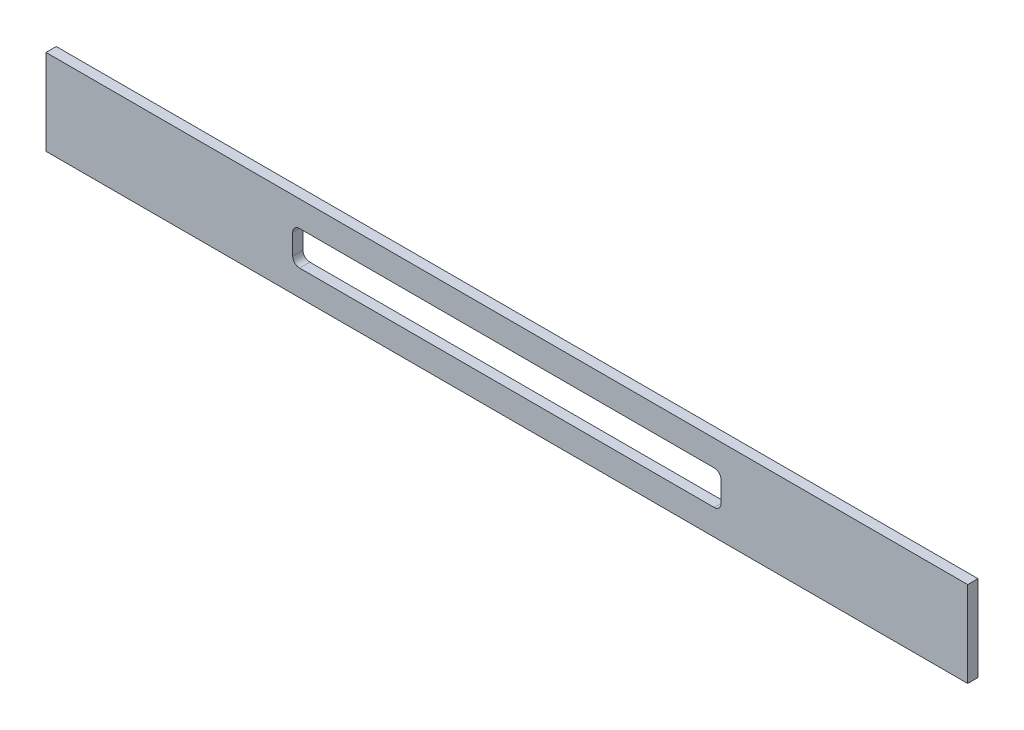
SolidWorks part; units mm, degrees
material "Клен"
ref_plane "Спереди" through (0, 0, 0) normal (0, 0, 1) x (1, 0, 0)
ref_plane "Сверху" through (0, 0, 0) normal (0, 1, 0) x (1, 0, 0)
ref_plane "Справа" through (0, 0, 0) normal (1, 0, 0) x (0, 0, -1)
sketch "Эскиз1" plane through (0, 0, 0) normal (0, 0, 1) x (1, 0, 0)
  line L0 (95.1697, 36.9253) -> (95.1697, -99.1193) construction
  line L1 (-173.8303, 7.2008) -> (364.1697, 7.2008)
  line L2 (-173.8303, 7.2008) -> (-173.8303, -42.7992)
  line L3 (-173.8303, -42.7992) -> (364.1697, -42.7992)
  line L4 (364.1697, 7.2008) -> (364.1697, -42.7992)
  line L5 (-25.8303, -7.7992) -> (216.1697, -7.7992)
  line L6 (-29.8303, -11.7992) -> (-29.8303, -23.7992)
  line L7 (-25.8303, -27.7992) -> (216.1697, -27.7992)
  line L8 (220.1697, -11.7992) -> (220.1697, -23.7992)
  line L9 (-29.8303, -7.7992) -> (220.1697, -27.7992) construction
  line L10 (-29.8303, -27.7992) -> (220.1697, -7.7992) construction
  arc A0 (216.1697, -27.7992) -> (220.1697, -23.7992) centre (216.1697, -23.7992) ccw
  arc A1 (216.1697, -7.7992) -> (220.1697, -11.7992) centre (216.1697, -11.7992) cw
  arc A2 (-25.8303, -7.7992) -> (-29.8303, -11.7992) centre (-25.8303, -11.7992) ccw
  arc A3 (-25.8303, -27.7992) -> (-29.8303, -23.7992) centre (-25.8303, -23.7992) cw
  point P4 (74.7377, -21.9819)
  dimension "D5" = 4
  dimension "D1" = 538
  dimension "D2" = 50
  dimension "D3" = 20
  dimension "D4" = 250
  dimension "D6" = 15
extrude "Бобышка-Вытянуть1" add sketch "Эскиз1" along normal blind 6
